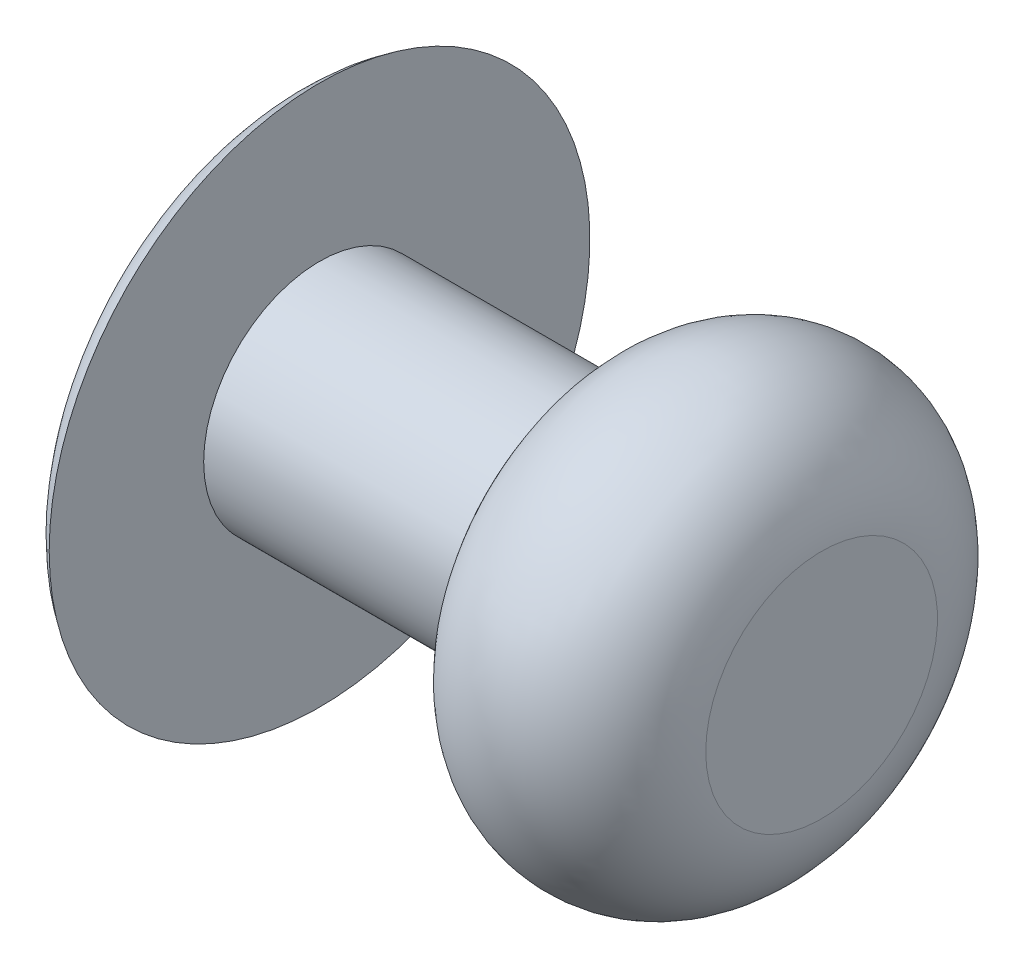
SolidWorks part; units mm, degrees
ref_plane "Plan de face" through (0, 0, 0) normal (0, 0, 1) x (1, 0, 0)
ref_plane "Plan de dessus" through (0, 0, 0) normal (0, 1, 0) x (1, 0, 0)
ref_plane "Plan de droite" through (0, 0, 0) normal (1, 0, 0) x (0, 0, -1)
sketch "Esquisse1" plane through (0, 0, 0) normal (0, 0, 1) x (1, 0, 0)
  line L0 (-91.1066, 0) -> (94.9883, 0) construction
  line L1 (-13.4906, 0) -> (-13.4906, 2.5)
  line L2 (-12.9389, 1.5) -> (-12.9389, 3.5)
  line L3 (-12.9389, 1.5) -> (-9.4389, 1.5)
  line L4 (-6.4389, 1.5) -> (-6.4389, 0)
  line L5 (-6.4389, 0) -> (-13.4906, 0)
  arc A0 (-12.9389, 3.5) -> (-13.4906, 2.5) centre (-12.3085, 2.5) ccw
  arc A1 (-6.4389, 1.5) -> (-9.4389, 1.5) centre (-7.9389, 1.4) ccw
  dimension "D1" = 2.5
  dimension "D2" = 1
  dimension "D3" = 3.5
  dimension "D4" = 1.5
  dimension "D5" = 1.5
  dimension "D6" = 3
  dimension "D7" = 0.1
revolve "Révolution1" add sketch "Esquisse1" angle 360 about L0
sketch "Esquisse2" plane through (-13.4906, 0, 0) normal (-1, 0, 0) x (0, 0, 1)
  circle A0 centre (0, 0) radius 1
  dimension "D1" = 2
extrude "Extrusion1" cut sketch "Esquisse2" against normal blind 4
